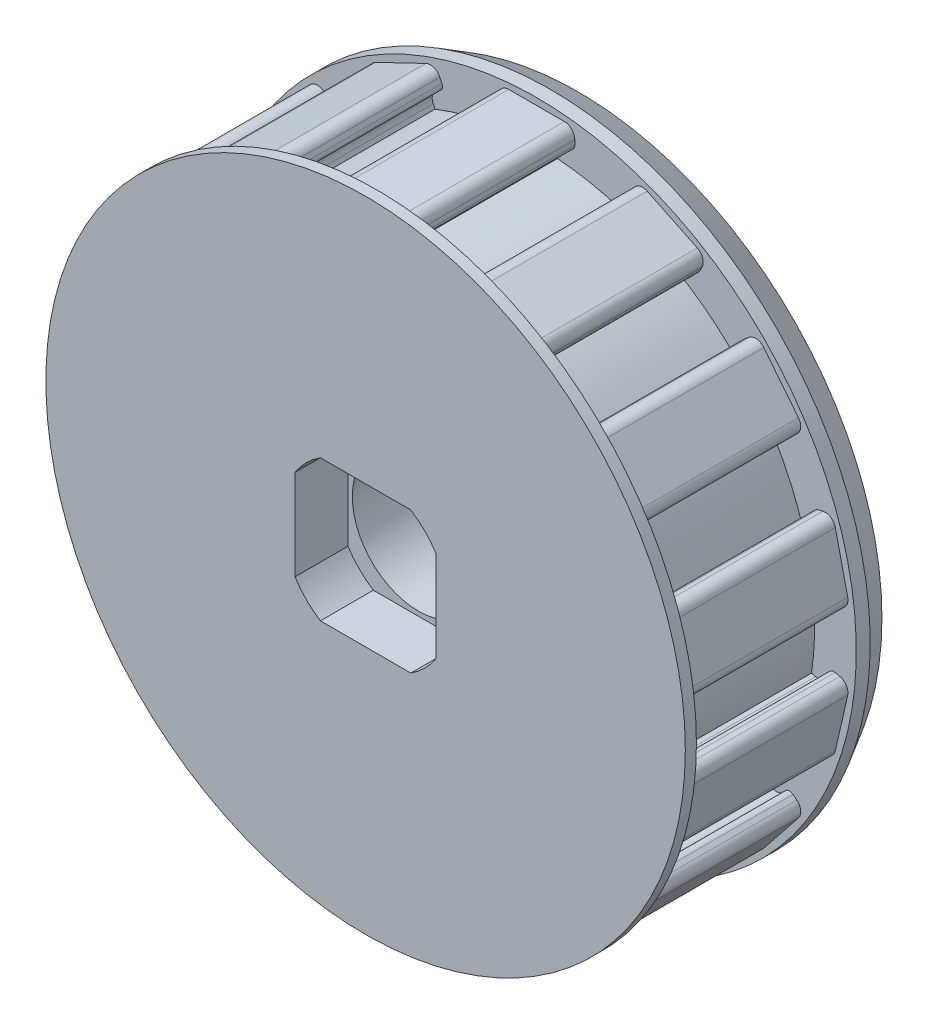
SolidWorks part; units mm, degrees
material "PE High Density"
ref_plane "Front Plane" through (0, 0, 0) normal (0, 0, 1) x (1, 0, 0)
ref_plane "Top Plane" through (0, 0, 0) normal (0, 1, 0) x (1, 0, 0)
ref_plane "Right Plane" through (0, 0, 0) normal (1, 0, 0) x (0, 0, -1)
sketch "Sketch1" plane through (0, 0, 0) normal (0, 0, 1) x (1, 0, 0)
  circle A0 centre (0, 0) radius 40
  circle A1 centre (0, 0) radius 9.525
  circle A2 centre (0, 0) radius 50 construction
  dimension "D1" = 80
  dimension "D2" = 19.05
  dimension "D3" = 100
extrude "Boss-Extrude1" add sketch "Sketch1" along normal blind 23
sketch "Sketch3" plane through (0, 0, 0) normal (0, 0, -1) x (-1, 0, 0)
  line L5 (-4, 45) -> (4, 45)
  line L6 (5.5, 43.5) -> (5.5, 42.8)
  line L11 (4.7, 42) -> (4.5, 42)
  line L12 (3, 40.5) -> (3, 35.9393)
  line L14 (3, 35.9393) -> (-3, 35.9393)
  line L15 (-3, 35.9393) -> (-3, 40.5)
  line L16 (-4.5, 42) -> (-4.7, 42)
  line L17 (-5.5, 42.8) -> (-5.5, 43.5)
  arc A0 (5.5, 43.5) -> (4, 45) centre (4, 43.5) ccw
  circle A1 centre (0, 0) radius 50 construction
  arc A2 (-5.5, 43.5) -> (-4, 45) centre (-4, 43.5) cw
  arc A3 (3, 40.5) -> (4.5, 42) centre (4.5, 40.5) cw
  arc A4 (-3, 40.5) -> (-4.5, 42) centre (-4.5, 40.5) ccw
  arc A5 (4.7, 42) -> (5.5, 42.8) centre (4.7, 42.8) ccw
  arc A6 (-5.5, 42.8) -> (-4.7, 42) centre (-4.7, 42.8) ccw
  dimension "D1" = 100
  dimension "D2" = 3
  dimension "D9" = 1.5
  dimension "D10" = 0.8
  dimension "D3" = 3
  dimension "D4" = 42
  dimension "D5" = 0
  dimension "D6" = 45
  dimension "D7" = 5.5
  dimension "D8" = 5.5
extrude "Boss-Extrude2" add sketch "Sketch3" against normal up to surface (23 mm away) contours L15 A4 L16 A6 L17 A2 L5 A0 L6 A5 L11 A3 L12 L14 up to face at (40, 0, 23)
pattern_circular "CirPattern1" count 14 over 360 about axis through (0, 0, 0) along (0, 0, 1) of "Boss-Extrude2"
sketch "Sketch2" plane through (0, 0, 23) normal (0, 0, 1) x (1, 0, 0)
  line L1 (-10.16, -10.16) -> (10.16, -10.16)
  line L2 (-10.16, -10.16) -> (-10.16, 10.16)
  line L3 (-10.16, 10.16) -> (10.16, 10.16)
  line L4 (10.16, -10.16) -> (10.16, 10.16)
  line L5 (-10.16, -10.16) -> (10.16, 10.16) construction
  line L6 (-10.16, 10.16) -> (10.16, -10.16) construction
  arc A0 (6.5068, 10.16) -> (10.16, 6.5068) centre (0, 0) cw
  arc A1 (-6.5068, 10.16) -> (-10.16, 6.5068) centre (0, 0) ccw
  arc A2 (-10.16, -6.5068) -> (-6.5068, -10.16) centre (0, 0) ccw
  arc A3 (6.5068, -10.16) -> (10.16, -6.5068) centre (0, 0) ccw
  point P0 (0, 0)
  dimension "D1" = 20.32
extrude "Cut-Extrude2" cut sketch "Sketch2" against normal blind 6.02 contours L1 A3 L4 A0 L3 A1 L2 A2
sketch "Sketch8" plane through (0, 0, 23) normal (0, 0, 1) x (1, 0, 0)
  line L36 (10.16, -6.5068) -> (10.16, 6.5068)
  line L37 (-6.5068, -10.16) -> (6.5068, -10.16)
  line L38 (-10.16, 6.5068) -> (-10.16, -6.5068)
  line L39 (6.5068, 10.16) -> (-6.5068, 10.16)
  line L40 (10.16, -6.5068) -> (10.16, 6.5068)
  line L41 (-6.5068, -10.16) -> (6.5068, -10.16)
  line L42 (-10.16, 6.5068) -> (-10.16, -6.5068)
  line L43 (6.5068, 10.16) -> (-6.5068, 10.16)
  circle A0 centre (0, 0) radius 46
  arc A30 (10.16, 6.5068) -> (6.5068, 10.16) centre (0, 0) ccw
  arc A31 (6.5068, -10.16) -> (10.16, -6.5068) centre (0, 0) ccw
  arc A32 (-10.16, -6.5068) -> (-6.5068, -10.16) centre (0, 0) ccw
  arc A33 (-6.5068, 10.16) -> (-10.16, 6.5068) centre (0, 0) ccw
  arc A34 (10.16, 6.5068) -> (6.5068, 10.16) centre (0, 0) ccw
  arc A35 (6.5068, -10.16) -> (10.16, -6.5068) centre (0, 0) ccw
  arc A36 (-10.16, -6.5068) -> (-6.5068, -10.16) centre (0, 0) ccw
  arc A37 (-6.5068, 10.16) -> (-10.16, 6.5068) centre (0, 0) ccw
  dimension "D2" = 92
  dimension "D1" = 0
extrude "Boss-Extrude3" add sketch "Sketch8" along normal blind 1.6
sketch "Sketch13" plane through (0, 0, 0) normal (0, 0, -1) x (-1, 0, 0)
  circle A0 centre (0, 0) radius 46
  dimension "D1" = 92
extrude "Boss-Extrude7" add sketch "Sketch13" along normal blind 6
sketch "Sketch11" plane through (0, 0, -6) normal (0, 0, -1) x (-1, 0, 0)
  circle A0 centre (0, 0) radius 27
  dimension "D1" = 54
extrude "Cut-Extrude4" cut sketch "Sketch11" against normal blind 13
chamfer "Chamfer1" distance 7.5 angle 60 1 edges at (-27, 0, -6)
chamfer "Chamfer2" distance 4 angle 30 1 edges at (-46, 0, -6)
sketch "Sketch14" plane through (0, 0, 7) normal (0, 0, -1) x (-1, 0, 0)
  circle A0 centre (0, 0) radius 14.5
  dimension "D1" = 29
extrude "Cut-Extrude5" cut sketch "Sketch14" against normal blind 1
